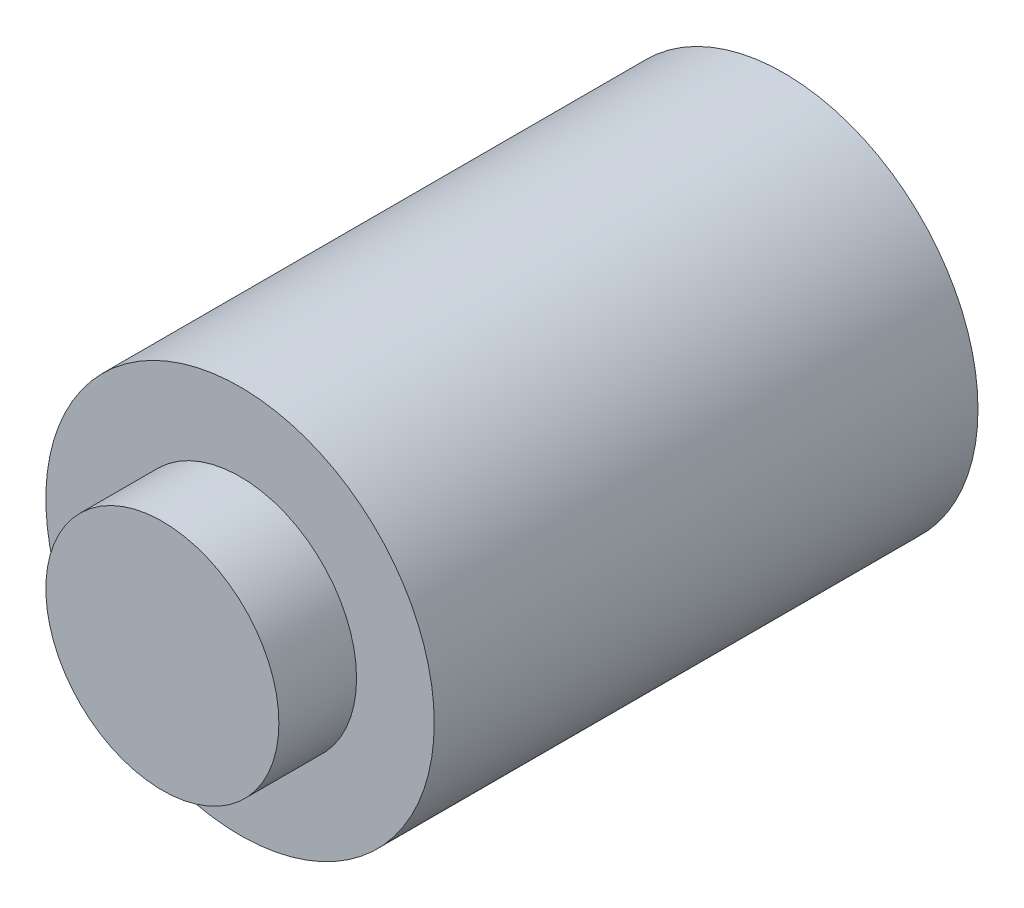
SolidWorks part; units mm, degrees
ref_plane "Piano frontale" through (0, 0, 0) normal (0, 0, 1) x (1, 0, 0)
ref_plane "Piano superiore" through (0, 0, 0) normal (0, 1, 0) x (1, 0, 0)
ref_plane "Piano destro" through (0, 0, 0) normal (1, 0, 0) x (0, 0, -1)
sketch "Schizzo1" plane through (0, 0, 0) normal (0, 0, 1) x (1, 0, 0)
  circle A0 centre (0, 0) radius 5
  dimension "D1" = 10
extrude "Estrusione-Estrusione1" add sketch "Schizzo1" along normal blind 14
sketch "Schizzo2" plane through (0, 0, 14) normal (0, 0, 1) x (1, 0, 0)
  circle A0 centre (0, 0) radius 3
  dimension "D1" = 6
extrude "Estrusione-Estrusione2" add sketch "Schizzo2" along normal blind 2
hole_wizard "Foro filettato M6-1" positions "Schizzo5" profile "Schizzo4" tap size "M6" standard "ISO"
sketch "Schizzo5" plane through (0, 0, 0) normal (0, 0, -1) x (-1, 0, 0)
  point P0 (0, 0)
sketch "Schizzo4" plane through (0, 0, 0) normal (1, 0, 0) x (0, 1, 0)
  line L0 (0, 0) -> (0, 7.5022)
  line L1 (0, 7.5022) -> (2.5, 6)
  line L2 (2.5, 6) -> (2.5, 1)
  line L3 (2.5, 1) -> (3.5, 0)
  line L5 (3.5, 0) -> (0, 0)
  line L6 (-2.5, 1) -> (-3.5, 0) construction
  line L10 (0, 7.5022) -> (-2.5, 6) construction
  line L11 (0, -6.35) -> (0, 107.95) construction
  dimension "Tap Drill Dia." = 5
  dimension "Tap Drill Depth" = 6
  dimension "Near C'Sink Dia." = 7
  dimension "Near C'Sink Angle" = 90
  dimension "Drill Angle" = 118
cosmetic thread "Filettatura del foro1" parameters "D1"=6, "D2"=6
